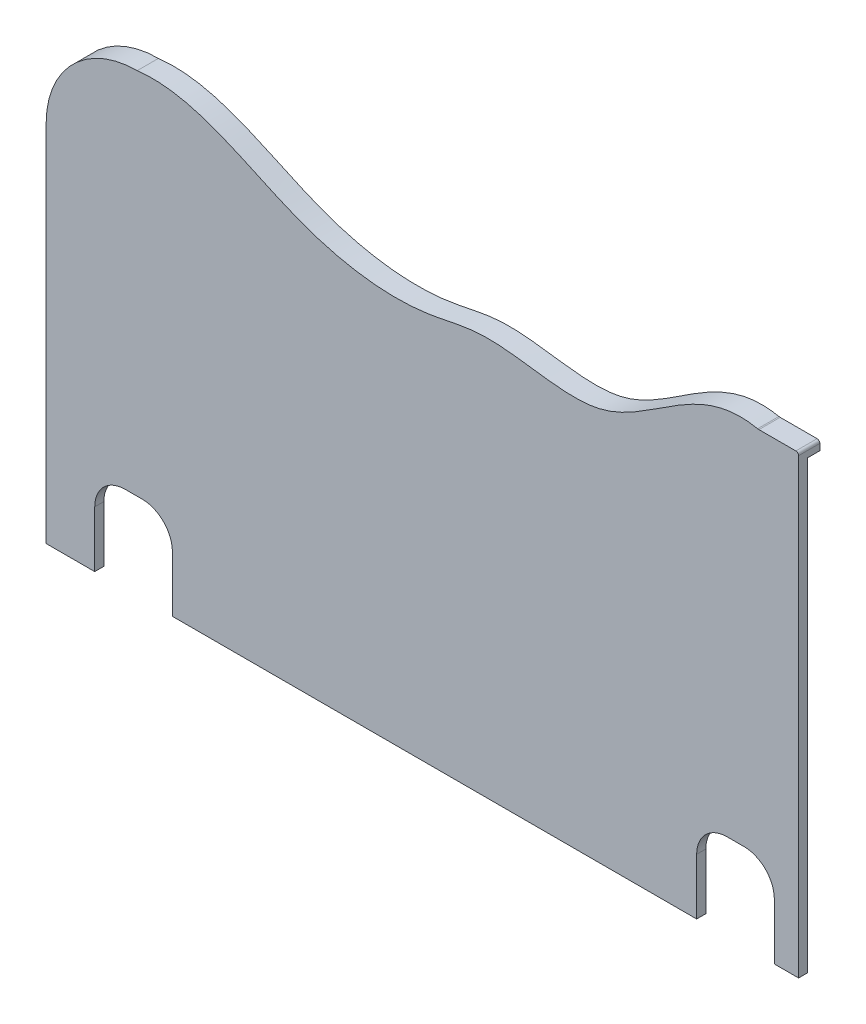
SolidWorks part; units mm, degrees
ref_plane "Front Plane" through (0, 0, 0) normal (0, 0, 1) x (1, 0, 0)
ref_plane "Top Plane" through (0, 0, 0) normal (0, 1, 0) x (1, 0, 0)
ref_plane "Right Plane" through (0, 0, 0) normal (1, 0, 0) x (0, 0, -1)
sketch "Sketch1" plane through (0, 0, 0) normal (0, 0, 1) x (1, 0, 0)
  line L0 (-124.7655, -62.4208) -> (-108.7655, -62.4208)
  line L1 (-108.7655, -62.4208) -> (-108.7617, -43.9208)
  line L2 (-98.7607, -33.9112) -> (-93.1607, -33.9082)
  line L3 (-83.1617, -43.8828) -> (-83.1655, -62.3828)
  line L4 (-83.1655, -62.3828) -> (89.6345, -62.3828)
  line L5 (89.6345, -62.3828) -> (89.6391, -43.9002)
  line L6 (99.6415, -33.9027) -> (105.2415, -33.9041)
  line L7 (115.2391, -43.9066) -> (115.2345, -62.4188)
  line L8 (115.2345, -62.4188) -> (123.2345, -62.4208)
  line L9 (123.2345, -62.4208) -> (123.2345, 86.6792)
  line L12 (-72.7655, 43.6172) -> (-72.7655, 39.6172) construction
  line L13 (-71.7655, 38.6172) -> (-65.7655, 38.6172) construction
  line L14 (-64.7655, 39.6172) -> (-64.7655, 43.6172) construction
  line L15 (-65.7655, 44.6172) -> (-71.7655, 44.6172) construction
  line L16 (79.2345, 39.6172) -> (79.2345, 43.6172) construction
  line L17 (72.2345, 38.6172) -> (78.2345, 38.6172) construction
  line L18 (71.2345, 43.6172) -> (71.2345, 39.6172) construction
  line L19 (78.2345, 44.6172) -> (72.2345, 44.6172) construction
  line L20 (-124.7655, -62.4208) -> (-124.7655, 57.5792)
  line L22 (-65.7655, 38.6172) -> (72.2345, 38.6172) construction
  line L23 (3.2345, 38.6172) -> (3.2345, 63.6172) construction
  line L24 (-147.7002, 63.6172) -> (183.6435, 63.6172) construction
  line L25 (110.1579, 87.5792) -> (122.3345, 87.5792)
  arc A0 (-98.7607, -33.9112) -> (-108.7617, -43.9208) centre (-98.7617, -43.9112) ccw
  arc A1 (-83.1617, -43.8828) -> (-93.1607, -33.9082) centre (-93.1617, -43.9082) ccw
  arc A2 (99.6415, -33.9027) -> (89.6391, -43.9002) centre (99.6391, -43.9027) ccw
  arc A3 (115.2391, -43.9066) -> (105.2415, -33.9041) centre (105.2391, -43.9041) ccw
  arc A5 (-72.7655, 39.6172) -> (-71.7655, 38.6172) centre (-71.7655, 39.6172) ccw construction
  arc A6 (-65.7655, 38.6172) -> (-64.7655, 39.6172) centre (-65.7655, 39.6172) ccw construction
  arc A7 (-64.7655, 43.6172) -> (-65.7655, 44.6172) centre (-65.7655, 43.6172) ccw construction
  arc A8 (-71.7655, 44.6172) -> (-72.7655, 43.6172) centre (-71.7655, 43.6172) ccw construction
  arc A9 (79.2345, 43.6172) -> (78.2345, 44.6172) centre (78.2345, 43.6172) ccw construction
  arc A10 (78.2345, 38.6172) -> (79.2345, 39.6172) centre (78.2345, 39.6172) ccw construction
  arc A11 (71.2345, 39.6172) -> (72.2345, 38.6172) centre (72.2345, 39.6172) ccw construction
  arc A12 (72.2345, 44.6172) -> (71.2345, 43.6172) centre (72.2345, 43.6172) ccw construction
  arc A13 (-124.7655, 57.5792) -> (-94.7655, 87.5792) centre (-94.7655, 57.5792) cw
  arc A14 (109.7492, 87.6215) -> (110.1579, 87.5792) centre (110.1579, 89.5792) ccw
  arc A15 (123.2345, 86.6792) -> (122.3345, 87.5792) centre (122.3345, 86.6792) ccw
  spline S0 degree 3 poles (-94.7655, 87.5792) (-74.9575, 89.9402) (-46.2376, 68.9543) (-6.6007, 63.2992) (25.0044, 72.0307) (58.0164, 59.3867) (84.0588, 84.5535) (102.3292, 89.1707) (109.7492, 87.6215) knots 0 0 0 0 0.273591 0.468641 0.542502 0.732723 0.90422 0.999913 0.999913 0.999913 0.999913
  point P57 (123.2345, 87.5792)
  dimension "D7" = 248
  dimension "D12" = 1
  dimension "D13" = 1
  dimension "D14" = 1
  dimension "D15" = 1
  dimension "D16" = 1
  dimension "D17" = 8
  dimension "D23" = 10
  dimension "D24" = 10
  dimension "D9" = 30
  dimension "D28" = 2
  dimension "D29" = 0.9
  dimension "D1" = 16
  dimension "D3" = 172.8
  dimension "D4" = 25.6
  dimension "D5" = 25.6
  dimension "D6" = 8
  dimension "D8" = 101
  dimension "D10" = 8
  dimension "D11" = 6
  dimension "D18" = 6
  dimension "D19" = 101
  dimension "D20" = 136
  dimension "D21" = 18.5
  dimension "D22" = 18.5
  dimension "D25" = 5.6
  dimension "D26" = 25
  dimension "D27" = 150
extrude "Boss-Extrude1" add sketch "Sketch1" along normal blind 3
sketch "Sketch2" plane through (0, 0, 0) normal (0, 0, -1) x (-1, 0, 0)
  line L32 (-3.2345, 63.6172) -> (-3.2345, 38.6172) construction
  line L33 (65.7655, 44.6172) -> (71.7655, 44.6172)
  line L34 (64.7655, 39.6172) -> (64.7655, 43.6172)
  line L35 (71.7655, 38.6172) -> (65.7655, 38.6172)
  line L36 (-79.2345, 43.6172) -> (-79.2345, 39.6172)
  line L37 (-78.2345, 38.6172) -> (-72.2345, 38.6172)
  line L38 (-71.2345, 39.6172) -> (-71.2345, 43.6172)
  line L39 (-72.2345, 44.6172) -> (-78.2345, 44.6172)
  line L40 (-79.2345, 43.6172) -> (-79.2345, 39.6172)
  line L41 (-78.2345, 38.6172) -> (-72.2345, 38.6172)
  line L42 (-71.2345, 39.6172) -> (-71.2345, 43.6172)
  line L43 (-72.2345, 44.6172) -> (-78.2345, 44.6172)
  line L44 (72.7655, 43.6172) -> (72.7655, 39.6172)
  arc A23 (64.7655, 43.6172) -> (65.7655, 44.6172) centre (65.7655, 43.6172) cw
  arc A24 (65.7655, 38.6172) -> (64.7655, 39.6172) centre (65.7655, 39.6172) cw
  arc A25 (72.7655, 39.6172) -> (71.7655, 38.6172) centre (71.7655, 39.6172) cw
  arc A26 (71.7655, 44.6172) -> (72.7655, 43.6172) centre (71.7655, 43.6172) cw
  arc A27 (-78.2345, 44.6172) -> (-79.2345, 43.6172) centre (-78.2345, 43.6172) ccw
  arc A28 (-79.2345, 39.6172) -> (-78.2345, 38.6172) centre (-78.2345, 39.6172) ccw
  arc A29 (-72.2345, 38.6172) -> (-71.2345, 39.6172) centre (-72.2345, 39.6172) ccw
  arc A30 (-71.2345, 43.6172) -> (-72.2345, 44.6172) centre (-72.2345, 43.6172) ccw
  arc A31 (-78.2345, 44.6172) -> (-79.2345, 43.6172) centre (-78.2345, 43.6172) ccw
  arc A32 (-79.2345, 39.6172) -> (-78.2345, 38.6172) centre (-78.2345, 39.6172) ccw
  arc A33 (-72.2345, 38.6172) -> (-71.2345, 39.6172) centre (-72.2345, 39.6172) ccw
  arc A34 (-71.2345, 43.6172) -> (-72.2345, 44.6172) centre (-72.2345, 43.6172) ccw
  dimension "D1" = 0
extrude "Boss-Extrude2" add sketch "Sketch2" along normal blind 3
sketch "Sketch3" plane through (0, 0, 0) normal (0, 0, -1) x (-1, 0, 0)
  line L24 (-110.1579, 84.5792) -> (-120.2345, 84.5792)
  line L25 (-120.2345, 84.5792) -> (-120.2345, -59.42)
  line L26 (-120.2345, -59.42) -> (-118.2352, -59.4195)
  line L27 (-118.2352, -59.4195) -> (-118.2391, -43.9073)
  line L28 (-105.2423, -30.9041) -> (-99.6423, -30.9027)
  line L29 (-86.6391, -43.8995) -> (-86.6352, -59.3828)
  line L30 (-86.6352, -59.3828) -> (80.1649, -59.3828)
  line L31 (80.1649, -59.3828) -> (80.1617, -43.8796)
  line L32 (93.1688, -30.9082) -> (98.7688, -30.9112)
  line L33 (111.7617, -43.9086) -> (111.7649, -59.4208)
  line L34 (111.7649, -59.4208) -> (121.7655, -59.4208)
  line L35 (121.7655, -59.4208) -> (121.7655, 57.5792)
  line L36 (-110.1579, 84.5792) -> (-120.2345, 84.5792)
  line L47 (121.7655, -59.4208) -> (121.7655, 57.5792)
  line L48 (-120.2345, 84.5792) -> (-123.2345, 84.5792)
  line L51 (121.7655, -59.4208) -> (121.7655, -62.4208)
  line L60 (-110.1579, 87.5792) -> (-122.3345, 87.5792)
  line L61 (-123.2345, 86.6792) -> (-123.2345, -62.4208)
  line L62 (-123.2345, -62.4208) -> (-115.2345, -62.4188)
  line L63 (-115.2345, -62.4188) -> (-115.2391, -43.9066)
  line L64 (-105.2415, -33.9041) -> (-99.6415, -33.9027)
  line L65 (-89.6391, -43.9002) -> (-89.6345, -62.3828)
  line L66 (-89.6345, -62.3828) -> (83.1655, -62.3828)
  line L67 (83.1655, -62.3828) -> (83.1617, -43.8828)
  line L68 (93.1671, -33.9082) -> (98.7672, -33.9112)
  line L69 (108.7617, -43.9092) -> (108.7655, -62.4208)
  line L70 (108.7655, -62.4208) -> (124.7655, -62.4208)
  line L71 (124.7655, -62.4208) -> (124.7655, 57.5792)
  line L72 (-110.1579, 87.5792) -> (-122.3345, 87.5792)
  line L73 (-123.2345, 86.6792) -> (-123.2345, 84.5792)
  line L82 (121.7655, -62.4208) -> (124.7655, -62.4208)
  line L83 (124.7655, -62.4208) -> (124.7655, 57.5792)
  arc A14 (121.7655, 57.5792) -> (94.592, 84.5787) centre (94.7655, 57.5792) ccw
  arc A15 (-110.1579, 84.5792) -> (-109.136, 84.6848) centre (-110.1579, 89.5792) ccw
  arc A16 (-105.2423, -30.9041) -> (-118.2391, -43.9073) centre (-105.2391, -43.9041) ccw
  arc A17 (-86.6391, -43.8995) -> (-99.6423, -30.9027) centre (-99.6391, -43.9027) ccw
  arc A18 (93.1688, -30.9082) -> (80.1617, -43.8796) centre (93.1617, -43.9082) ccw
  arc A19 (111.7617, -43.9086) -> (98.7688, -30.9112) centre (98.7617, -43.9112) ccw
  arc A20 (121.7655, 57.5792) -> (94.592, 84.5787) centre (94.7655, 57.5792) ccw
  arc A21 (-110.1579, 84.5792) -> (-109.136, 84.6848) centre (-110.1579, 89.5792) ccw
  arc A33 (124.7655, 57.5792) -> (94.7655, 87.5792) centre (94.7655, 57.5792) ccw
  arc A34 (-110.1579, 87.5792) -> (-109.7492, 87.6215) centre (-110.1579, 89.5792) ccw
  arc A35 (-122.3345, 87.5792) -> (-123.2345, 86.6792) centre (-122.3345, 86.6792) ccw
  arc A36 (-105.2415, -33.9041) -> (-115.2391, -43.9066) centre (-105.2391, -43.9041) ccw
  arc A37 (-89.6391, -43.9002) -> (-99.6415, -33.9027) centre (-99.6391, -43.9027) ccw
  arc A38 (93.1671, -33.9082) -> (83.1617, -43.8828) centre (93.1617, -43.9082) ccw
  arc A39 (108.7617, -43.9092) -> (98.7672, -33.9112) centre (98.7617, -43.9112) ccw
  arc A40 (124.7655, 57.5792) -> (94.7655, 87.5792) centre (94.7655, 57.5792) ccw
  arc A41 (-110.1579, 87.5792) -> (-109.7492, 87.6215) centre (-110.1579, 89.5792) ccw
  arc A42 (-122.3345, 87.5792) -> (-123.2345, 86.6792) centre (-122.3345, 86.6792) ccw
  spline S2 degree 3 poles (-8.5184, 3080.7776) (187.4768, -10.7148) (136.7615, 81.2382) (92.3372, 84.7958) (91.7752, 84.8286) (90.0919, 84.8911) (88.9734, 84.8849) (85.6282, 84.7326) (83.412, 84.4523) (80.1048, 83.811) (79.0049, 83.5605) (76.8113, 82.9953) (75.7266, 82.683) (72.502, 81.6736) (70.3917, 80.9044) (64.1322, 78.4212) (60.0535, 76.5345) (53.929, 73.7208) (51.8867, 72.7847) (47.7789, 70.9694) (45.7123, 70.0899) (41.5524, 68.4459) (39.4571, 67.6838) (35.229, 66.3058) (33.097, 65.687) (26.6444, 64.0507) (22.2679, 63.2512) (16.6878, 62.6789) (15.5638, 62.5858) (13.3168, 62.4458) (12.1953, 62.3989) (8.837, 62.3286) (6.6064, 62.3756) (2.1624, 62.6662) (-0.0509, 62.91) (-4.4591, 63.6071) (-6.6541, 64.06) (-11.0464, 64.9382) (-13.2451, 65.3628) (-16.5383, 65.773) (-17.6354, 65.869) (-19.8281, 65.9672) (-20.9238, 65.9737) (-24.2094, 65.8971) (-26.3979, 65.7187) (-30.7731, 65.2476) (-32.9598, 64.9543) (-37.3332, 64.3726) (-39.5199, 64.0839) (-43.8984, 63.6279) (-46.0902, 63.4602) (-49.3857, 63.3954) (-50.4856, 63.4051) (-52.1379, 63.4803) (-52.6891, 63.5155) (-53.7925, 63.6087) (-54.3459, 63.6668) (-55.9984, 63.8783) (-57.0838, 64.0677) (-59.2188, 64.5542) (-60.2682, 64.8515) (-63.3706, 65.8809) (-65.3777, 66.7503) (-68.3276, 68.2362) (-69.3013, 68.7623) (-71.2204, 69.852) (-72.1677, 70.4166) (-76.8643, 73.3045) (-80.4931, 75.8229) (-85.1826, 78.7223) (-86.1283, 79.2895) (-88.0447, 80.3836) (-89.0146, 80.91) (-91.9605, 82.3952) (-93.976, 83.2637) (-97.1307, 84.2559) (-98.2085, 84.5346) (-100.3668, 84.9536) (-101.4523, 85.096) (-103.6373, 85.2344) (-104.7367, 85.2304) (-200.88, 78.2027) (-237.7252, -488.9183) (2122.5649, 2067.3293) knots -0.600847 -0.600847 -0.600847 -0.600847 0.007813 0.007813 0.015625 0.015625 0.03125 0.03125 0.0625 0.0625 0.078125 0.078125 0.09375 0.09375 0.125 0.125 0.1875 0.1875 0.21875 0.21875 0.25 0.25 0.28125 0.28125 0.3125 0.3125 0.375 0.375 0.390625 0.390625 0.40625 0.40625 0.4375 0.4375 0.46875 0.46875 0.5 0.5 0.53125 0.53125 0.546875 0.546875 0.5625 0.5625 0.59375 0.59375 0.625 0.625 0.65625 0.65625 0.6875 0.6875 0.703125 0.703125 0.710938 0.710938 0.71875 0.71875 0.734375 0.734375 0.75 0.75 0.78125 0.78125 0.796875 0.796875 0.8125 0.8125 0.875 0.875 0.890625 0.890625 0.90625 0.90625 0.9375 0.9375 0.953125 0.953125 0.96875 0.96875 0.984375 0.984375 2.326185 2.326185 2.326185 2.326185 only from (94.592, 84.5787) to (-109.136, 84.6848)
  spline S3 degree 3 poles (94.592, 84.5787) (94.0273, 84.646) (93.4632, 84.7056) (92.3372, 84.7958) (91.7752, 84.8286) (90.0919, 84.8911) (88.9734, 84.8849) (85.6282, 84.7326) (83.412, 84.4523) (80.1048, 83.811) (79.0049, 83.5605) (76.8113, 82.9953) (75.7266, 82.683) (72.502, 81.6736) (70.3917, 80.9044) (64.1322, 78.4212) (60.0535, 76.5345) (53.929, 73.7208) (51.8867, 72.7847) (47.7789, 70.9694) (45.7123, 70.0899) (41.5524, 68.4459) (39.4571, 67.6838) (35.229, 66.3058) (33.097, 65.687) (26.6444, 64.0507) (22.2679, 63.2512) (16.6878, 62.6789) (15.5638, 62.5858) (13.3168, 62.4458) (12.1953, 62.3989) (8.837, 62.3286) (6.6064, 62.3756) (2.1624, 62.6662) (-0.0509, 62.91) (-4.4591, 63.6071) (-6.6541, 64.06) (-11.0464, 64.9382) (-13.2451, 65.3628) (-16.5383, 65.773) (-17.6354, 65.869) (-19.8281, 65.9672) (-20.9238, 65.9737) (-24.2094, 65.8971) (-26.3979, 65.7187) (-30.7731, 65.2476) (-32.9598, 64.9543) (-37.3332, 64.3726) (-39.5199, 64.0839) (-43.8984, 63.6279) (-46.0902, 63.4602) (-49.3857, 63.3954) (-50.4856, 63.4051) (-52.1379, 63.4803) (-52.6891, 63.5155) (-53.7925, 63.6087) (-54.3459, 63.6668) (-55.9984, 63.8783) (-57.0838, 64.0677) (-59.2188, 64.5542) (-60.2682, 64.8515) (-63.3706, 65.8809) (-65.3777, 66.7503) (-68.3276, 68.2362) (-69.3013, 68.7623) (-71.2204, 69.852) (-72.1677, 70.4166) (-76.8643, 73.3045) (-80.4931, 75.8229) (-85.1826, 78.7223) (-86.1283, 79.2895) (-88.0447, 80.3836) (-89.0146, 80.91) (-91.9605, 82.3952) (-93.976, 83.2637) (-97.1307, 84.2559) (-98.2085, 84.5346) (-100.3668, 84.9536) (-101.4523, 85.096) (-103.6373, 85.2344) (-104.7367, 85.2304) (-106.95, 85.0686) (-108.0488, 84.9118) (-109.136, 84.6848) knots 0 0 0 0 0.007813 0.007813 0.015625 0.015625 0.03125 0.03125 0.0625 0.0625 0.078125 0.078125 0.09375 0.09375 0.125 0.125 0.1875 0.1875 0.21875 0.21875 0.25 0.25 0.28125 0.28125 0.3125 0.3125 0.375 0.375 0.390625 0.390625 0.40625 0.40625 0.4375 0.4375 0.46875 0.46875 0.5 0.5 0.53125 0.53125 0.546875 0.546875 0.5625 0.5625 0.59375 0.59375 0.625 0.625 0.65625 0.65625 0.6875 0.6875 0.703125 0.703125 0.710938 0.710938 0.71875 0.71875 0.734375 0.734375 0.75 0.75 0.78125 0.78125 0.796875 0.796875 0.8125 0.8125 0.875 0.875 0.890625 0.890625 0.90625 0.90625 0.9375 0.9375 0.953125 0.953125 0.96875 0.96875 0.984375 0.984375 1 1 1 1
  spline S5 degree 3 poles (1021.8714, -2760.6303) (188.7299, 315.7118) (137.3719, 81.9565) (6.6007, 63.2992) (-25.0044, 72.0307) (-58.0164, 59.3867) (-138.0114, 136.692) (-270.3935, -4.9167) (-1058.3049, -2754.9617) knots -1.247334 -1.247334 -1.247334 -1.247334 0.273591 0.468641 0.542502 0.732723 0.90422 1.947542 1.947542 1.947542 1.947542 only from (94.7655, 87.5792) to (-109.7492, 87.6215)
  spline S6 degree 3 poles (94.7655, 87.5792) (74.9575, 89.9402) (46.2376, 68.9543) (6.6007, 63.2992) (-25.0044, 72.0307) (-58.0164, 59.3867) (-84.0588, 84.5535) (-102.3292, 89.1707) (-109.7492, 87.6215) knots 0 0 0 0 0.273591 0.468641 0.542502 0.732723 0.90422 0.999913 0.999913 0.999913 0.999913
  dimension "D1" = 3
  dimension "D2" = 0
extrude "Boss-Extrude5" add sketch "Sketch3" along normal blind 4
